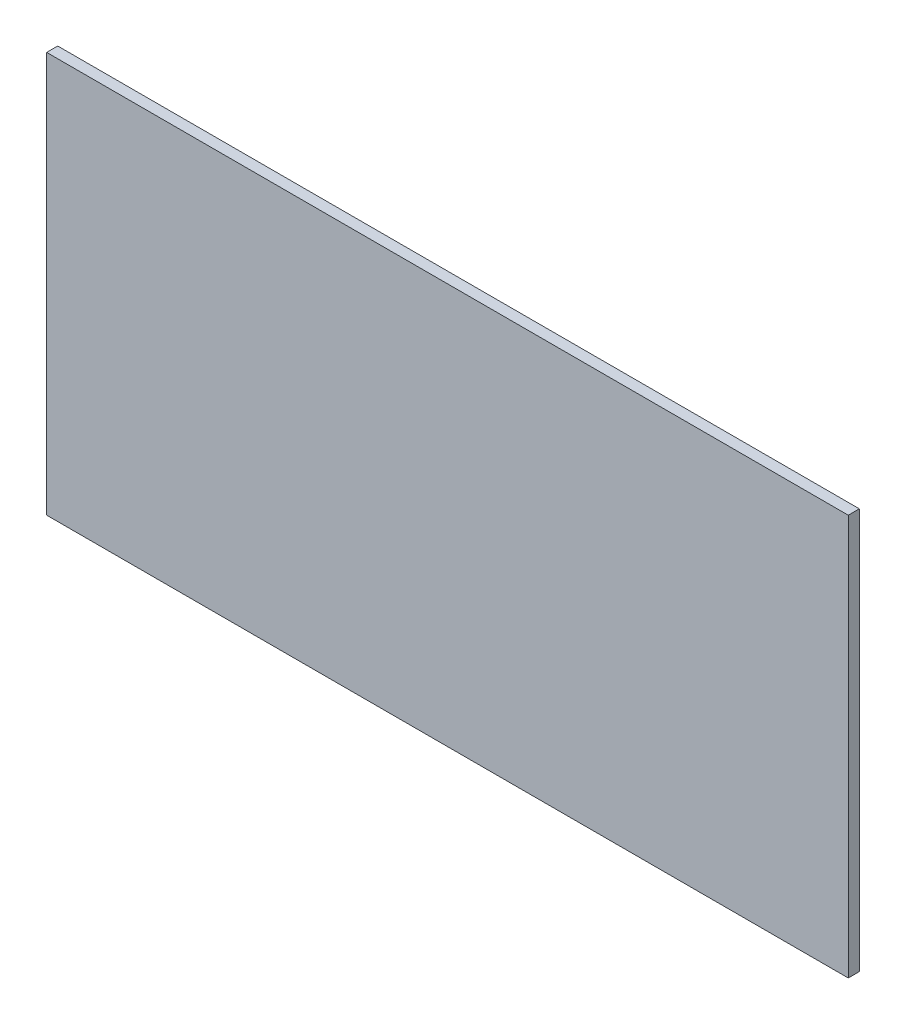
SolidWorks part; units mm, degrees
ref_plane "Alzado" through (0, 0, 0) normal (0, 0, 1) x (1, 0, 0)
ref_plane "Planta" through (0, 0, 0) normal (0, 1, 0) x (1, 0, 0)
ref_plane "Vista lateral" through (0, 0, 0) normal (1, 0, 0) x (0, 0, -1)
sketch "Sketch1" plane through (0, 0, 0) normal (0, 0, 1) x (1, 0, 0)
  line L1 (460, -230) -> (-460, -230)
  line L2 (460, -230) -> (460, 230)
  line L3 (460, 230) -> (-460, 230)
  line L4 (-460, -230) -> (-460, 230)
  line L5 (460, -230) -> (-460, 230) construction
  line L6 (460, 230) -> (-460, -230) construction
  point P0 (0, 0)
  dimension "D1" = 460
  dimension "D2" = 920
extrude "Boss-Extrude1" add sketch "Sketch1" along normal blind 12.7
